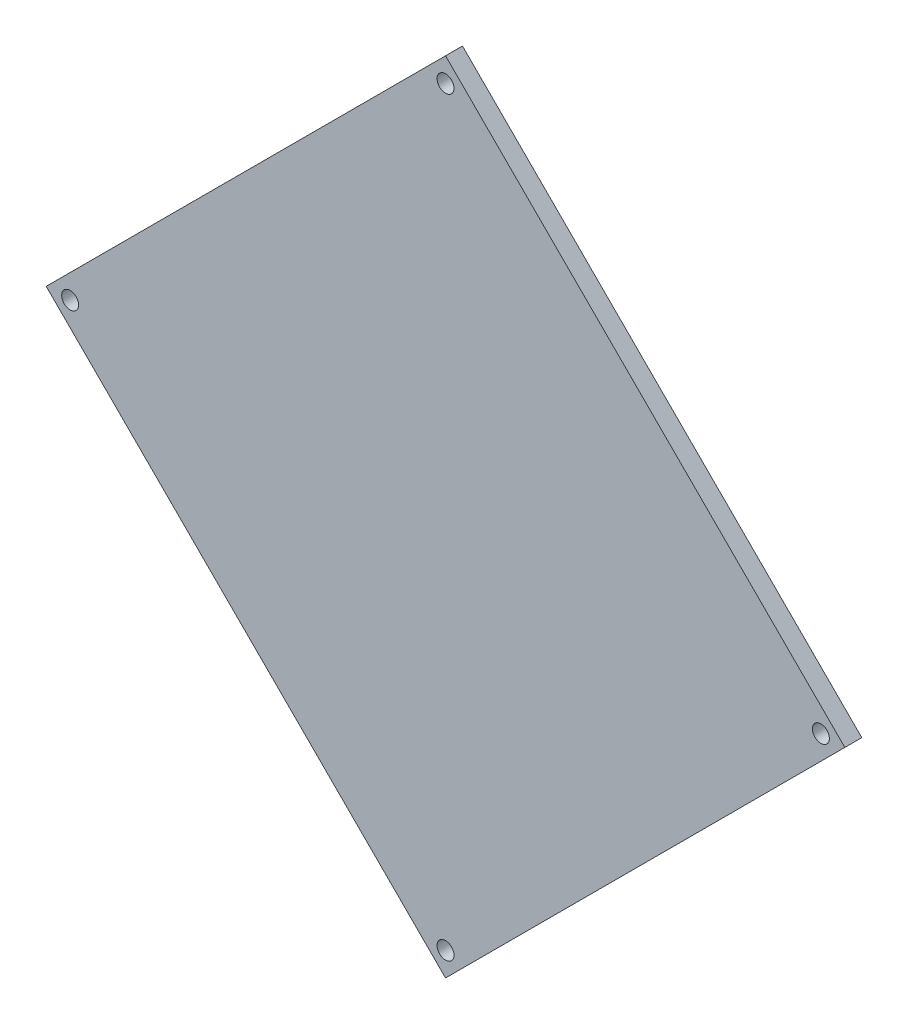
SolidWorks part; units mm, degrees
ref_plane "前视基准面" through (0, 0, 0) normal (0, 0, 1) x (1, 0, 0)
ref_plane "上视基准面" through (0, 0, 0) normal (0, 1, 0) x (1, 0, 0)
ref_plane "右视基准面" through (0, 0, 0) normal (1, 0, 0) x (0, 0, -1)
other "Configuration Table"
sketch "草图1" plane through (0, 0, 0) normal (0, 0, 1) x (1, 0, 0)
  line L0 (0, 0) -> (56.4362, 56.4362) construction
  line L1 (70.7107, 0) -> (0, 70.7107)
  line L2 (0, 70.7107) -> (-70.7107, 0)
  line L3 (-70.7107, 0) -> (0, -70.7107)
  line L4 (0, -70.7107) -> (70.7107, 0)
  line L5 (0, 0) -> (-84.1601, 84.1601) construction
  line L6 (0, 36.2508) -> (0, -34.189) construction
  circle A0 centre (0, 0) radius 50 construction
  circle A1 centre (0, 0) radius 66.468 construction
  circle A2 centre (0, 66.468) radius 1.5
  circle A3 centre (66.468, 0) radius 1.5
  circle A4 centre (0, 0) radius 66.468 construction
  circle A5 centre (0, -66.468) radius 1.5
  circle A6 centre (0, 0) radius 66.468 construction
  circle A7 centre (-66.468, 0) radius 1.5
  circle A8 centre (0, 0) radius 66.468 construction
  point P26 (0, 0)
  dimension "D3" = 47
  dimension "D4" = 3
  dimension "D1" = 100
  dimension "D2" = 47
  dimension "D5" = 45
  dimension "D6" = 4
extrude "凸台-拉伸1" add sketch "草图1" along normal blind 3
